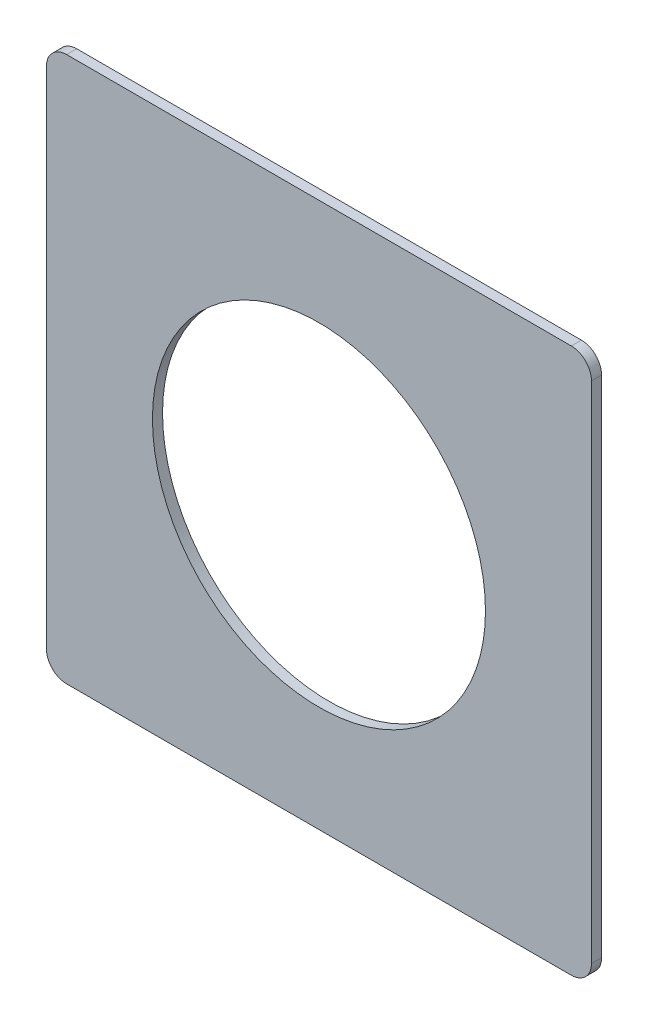
SolidWorks part; units mm, degrees
ref_plane "Front Plane" through (0, 0, 0) normal (0, 0, 1) x (1, 0, 0)
ref_plane "Top Plane" through (0, 0, 0) normal (0, 1, 0) x (1, 0, 0)
ref_plane "Right Plane" through (0, 0, 0) normal (1, 0, 0) x (0, 0, -1)
sketch "Sketch1" plane through (0, 0, 0) normal (0, 0, 1) x (1, 0, 0)
  line L0 (-158.75, 158.75) -> (158.75, -158.75) construction
  line L1 (-158.75, 171.45) -> (158.75, 171.45)
  line L2 (-171.45, 158.75) -> (-171.45, -158.75)
  line L3 (-158.75, -171.45) -> (158.75, -171.45)
  line L4 (171.45, 158.75) -> (171.45, -158.75)
  line L5 (-171.45, 171.45) -> (171.45, 171.45) construction
  arc A0 (158.75, 171.45) -> (171.45, 158.75) centre (158.75, 158.75) cw
  arc A1 (158.75, -171.45) -> (171.45, -158.75) centre (158.75, -158.75) ccw
  arc A2 (-171.45, -158.75) -> (-158.75, -171.45) centre (-158.75, -158.75) ccw
  arc A3 (-158.75, 171.45) -> (-171.45, 158.75) centre (-158.75, 158.75) ccw
  dimension "D1" = 12.7
extrude "Boss-Extrude1" add sketch "Sketch1" along normal blind 6.35
sketch "Sketch2" plane through (0, 0, 6.35) normal (0, 0, 1) x (1, 0, 0)
  circle A0 centre (0, 0) radius 104.7648
  circle A1 centre (0, 0) radius 104.5108 construction
  dimension "D1" = 0.254
extrude "Cut-Extrude1" cut sketch "Sketch2" against normal through all
